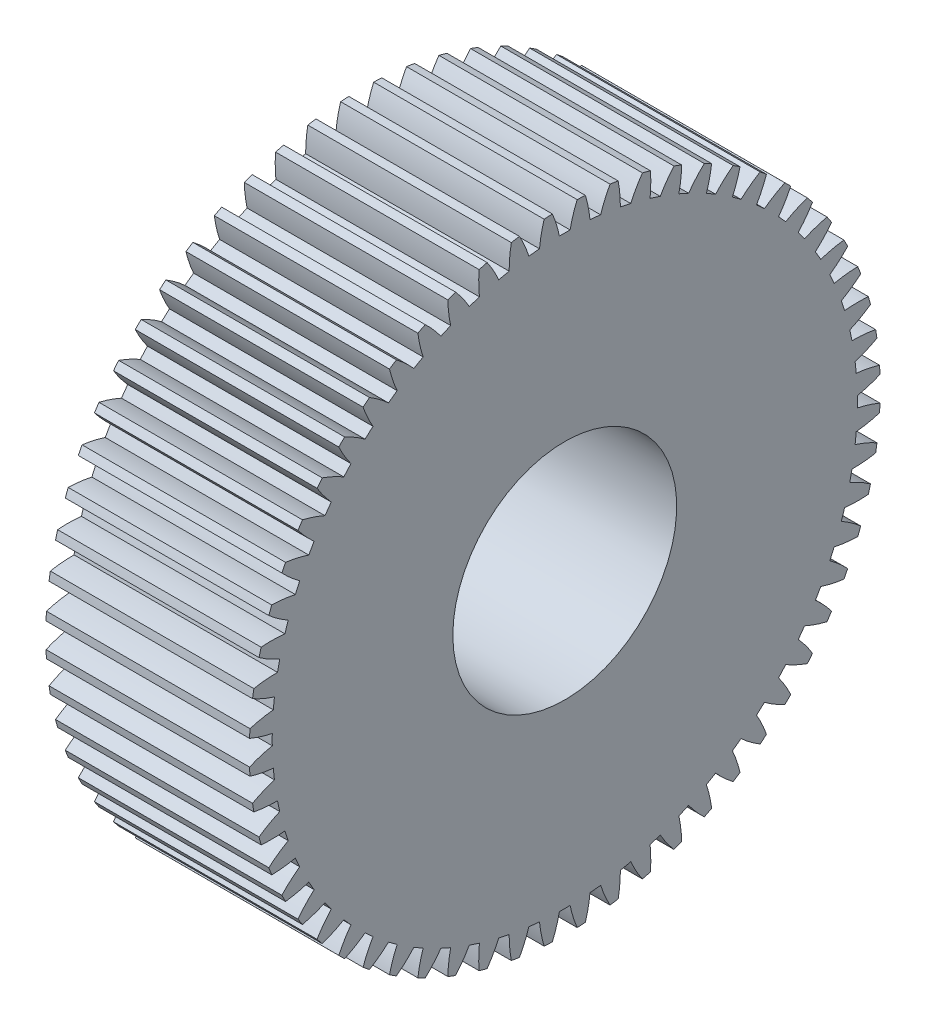
SolidWorks part; units mm, degrees
ref_plane "Plane1" through (0, 0, 0) normal (0, 0, 1) x (1, 0, 0)
ref_plane "Plane2" through (0, 0, 0) normal (0, 1, 0) x (1, 0, 0)
ref_plane "Plane3" through (0, 0, 0) normal (1, 0, 0) x (0, 0, -1)
other "Configuration Table"
sketch "HoldingSke" plane through (0, 0, 0) normal (0, 1, 0) x (1, 0, 0)
  line L0 (0, 0) -> (1, -1.7321)
  line L1 (-15, 0) -> (100, 0) construction
  line L2 (0, 0) -> (-2.1039, 2.3779)
  line L3 (0, 0) -> (-11.863, 4.5341)
  line L4 (0, 0) -> (4.318, 7.479)
  line L5 (0, 0) -> (-46.8476, -17.4728)
  line L6 (0, 0) -> (-8.2896, -5.593)
  line L7 (-2.1039, 2.3779) -> (8.6586, 51.2059)
  line L8 (-76.2, 54.61) -> (-74.4, 54.61)
  line L9 (-67.7845, 28.3722) -> (-49.3413, 33.142)
  line L10 (-76.2, 71.12) -> (104.1128, 71.12)
  line L11 (0, 0) -> (-10, 0)
  line L12 (-76.2, 101.6) -> (-76.181, 101.6)
  line L13 (24.9733, 27.94) -> (52.9518, 28.4284)
  line L14 (24.9733, 27.94) -> (24.9743, 27.94)
  line L15 (24.9733, 27.94) -> (100.4006, 29.5858)
  line L16 (-63.627, -0.5) -> (-12.827, -0.5)
  circle A0 centre (0, 0) radius 5.5
  circle A1 centre (0, 0) radius 14.374
  circle A2 centre (0, 0) radius 37.5
  circle A3 centre (0, 0) radius 5.5
  dimension "MHD" = 28.748
  dimension "Hub_dia" = 75
  dimension "Bore" = 11
  dimension "MBD" = 11
  dimension "Num_teeth" = 60
  dimension "Pitch" = 2
  dimension "Overall_len" = 50
  dimension "Show_teeth" = 60
  dimension "Thickness" = 10
  dimension "OAL" = 50.0001
  dimension "T_dim" = 1.8
  dimension "Ap" = 14.5
  dimension "H" = 19.05
  dimension "Pitch_radius" = 180.3128
  dimension "Width" = 10
  dimension "Backlash" = 0.019
  dimension "Addendum_fac" = 1
  dimension "Dedendum_fac" = 1.25
  dimension "Clearance_fac" = 0.25
  dimension "Dedendum_add" = 0.001
  dimension "Module" = 0.5
sketch "BasProSke" plane through (0, 0, 0) normal (0, 1, 0) x (1, 0, 0)
  line L0 (-10, 0) -> (60, 0) construction
  line L1 (0, 0) -> (0, 15.5)
  line L2 (0, 0) -> (10, 0)
  line L3 (10, 0) -> (10, 15.5)
  line L4 (10, 15.5) -> (0, 15.5)
  dimension "Thickness" = 10
  dimension "Diameter" = 31
revolve "Base-Revolve" add sketch "BasProSke" angle 360 about L0
sketch "TooCutSke" plane through (0, 0, 0) normal (1, 0, 0) x (0, 0, -1)
  line L1 (0, 0) -> (0, 107) construction
  line L2 (0, 0) -> (-0.4259, 14.994) construction
  line L3 (0, 0) -> (-1.5696, 29.9503) construction
  line L4 (-0.4259, 14.994) -> (-0.7848, 14.9751) construction
  arc A0 (0.2624, 14.3716) -> (-0.2624, 14.3716) centre (0, 0) ccw
  arc A1 (0.6193, 15.513) -> (-0.6193, 15.513) centre (0, 0) ccw
  circle A2 centre (0, 0) radius 15 construction
  circle A3 centre (0, 0) radius 14.5222 construction
  arc A4 (-0.2624, 14.3716) -> (-0.6193, 15.513) centre (-6.139, 13.1608) ccw
  arc A5 (0.6193, 15.513) -> (0.2624, 14.3716) centre (6.139, 13.1608) ccw
  dimension "Root_dia" = 28.748
  dimension "Overcut_dia" = 31.0508
  dimension "Pitch_dia" = 30
  dimension "Base_dia" = 29.0444
  dimension "Flank_rad" = 6
  dimension "Half_ang" = 3
  dimension "Half_CT" = 0.3594
extrude "ToothCut" cut sketch "TooCutSke" along normal through all
fillet "Breaks" [suppressed] radius 0.01
fillet "RootFillets" [suppressed] radius 0.126
pattern_circular "TeethCuts" count 60 every 6 about axis through (-10, 0, 0) along (1, 0, 0) of "ToothCut", "RootFillets", "Breaks"
sketch "HubNeaOneSke" plane through (0, 0, 0) normal (-1, 0, 0) x (0, 0, 1)
  circle A0 centre (0, 0) radius 14.374
  dimension "Diameter" = 28.748
extrude "HubNearOne" [suppressed] add sketch "HubNeaOneSke" along normal blind 40.0001
sketch "HubNeaBotSke" plane through (0, 0, 0) normal (-1, 0, 0) x (0, 0, 1)
  circle A0 centre (0, 0) radius 14.374
  dimension "Diameter" = 28.748
extrude "HubNearBoth" [suppressed] add sketch "HubNeaBotSke" along normal blind 20
ref_plane "FarPln" through (10, 0, 0) normal (1, 0, 0) x (0, 0, -1)
sketch "HubFarSke" plane through (10, 0, 0) normal (1, 0, 0) x (0, 0, -1)
  circle A0 centre (0, 0) radius 14.374
  dimension "Diameter" = 28.748
extrude "HubFar" [suppressed] add sketch "HubFarSke" along normal blind 20
sketch "BorSke" plane through (0, 0, 0) normal (1, 0, 0) x (0, 0, -1)
  circle A0 centre (0, 0) radius 5.5
  dimension "Diameter" = 11
extrude "Bore" cut sketch "BorSke" along normal mid plane 100.0001
sketch "KeySke" plane through (0, 0, 0) normal (1, 0, 0) x (0, 0, -1)
  line L0 (-2, 0) -> (-2, 7.3)
  line L1 (-2, 7.3) -> (2, 7.3)
  line L2 (2, 7.3) -> (2, 0)
  line L3 (0, 0) -> (0, 34) construction
  line L4 (-2, 0) -> (2, 0)
  dimension "Offset" = 7.3
  dimension "Width" = 4
extrude "Keyway" [suppressed] cut sketch "KeySke" along normal mid plane 100.0001
pattern_circular "Keyway2" [suppressed] count 2 every 90 about axis through (-10, 0, 0) along (1, 0, 0)
equation "' \"Module@HoldingSke\" = 6.35"
equation "' \"Num_teeth@HoldingSke\" = 12"
equation "' \"Ap@HoldingSke\" =  20"
equation "' \"Ap@HoldingSke\" = 20"
equation "' \"Width@HoldingSke\" = 0.5 * 25.4"
equation "' \"Hub_dia@HoldingSke\"= 1 * 25.4"
equation "' \"Hub_dia@HoldingSke\" = 1 * 25.4"
equation "' \"Overall_len@HoldingSke\" = 1.0 * 25.4"
equation "' \"Bore@HoldingSke\" = 0.75 * 25.4"
equation "' \"T_dim@HoldingSke\" = 0.1 * 25.4"
equation "' \"Width@KeySke\" = 0.25 * 25.4"
equation "' \"Show_teeth@HoldingSke\" = 13"
equation "' \"Backlash@HoldingSke\" = 0.009 * 25.4"
equation "' \"Addendum_fac@HoldingSke\" = 1.0"
equation "' \"Dedendum_fac@HoldingSke\" = 1.25"
equation "' \"Dedendum_add@HoldingSke\" = 0.00005 * 25.4"
equation "' \"Clearance_fac@HoldingSke\" = 0.25"
equation "\"Pitch@HoldingSke\" = 1 / \"Module@HoldingSke\""
equation "\"Overcut_dia@TooCutSke\" = (\"Num_teeth@HoldingSke\" + 2 * \"Addendum_fac@HoldingSke\") / \"Pitch@HoldingSke\" + 0.002 * 25.4"
equation "\"Pitch_dia@TooCutSke\" = \"Num_teeth@HoldingSke\" / \"Pitch@HoldingSke\""
equation "\"Base_dia@TooCutSke\" = \"Num_teeth@HoldingSke\" / \"Pitch@HoldingSke\" * cos((\"Ap@HoldingSke\"  * 3.14159265 / 180))"
equation "\"Root_dia@TooCutSke\" = (\"Num_teeth@HoldingSke\" + 2) / \"Pitch@HoldingSke\" - 2 * (\"Addendum_fac@HoldingSke\" + \"Dedendum_fac@HoldingSke\") / \"Pitch@HoldingSke\" - \"Dedendum_add@HoldingSke\" * 2"
equation "\"Half_ang@TooCutSke\" = 180 / \"Num_teeth@HoldingSke\""
equation "\"Half_CT@TooCutSke\" = \"Num_teeth@HoldingSke\" / \"Pitch@HoldingSke\" * sin((3.14159265 / 2 / \"Num_teeth@HoldingSke\")) / 2 - 7 * \"Backlash@HoldingSke\" / 4"
equation "\"Flank_rad@TooCutSke\" = \"Num_teeth@HoldingSke\" / \"Pitch@HoldingSke\" / 5"
equation "\"Radius@RootFillets\" = \"Clearance_fac@HoldingSke\" / \"Pitch@HoldingSke\" + \"Dedendum_add@HoldingSke\""
equation "\"Break_rad@Breaks\" = 0.02 / \"Pitch@HoldingSke\""
equation "\"Thickness@HoldingSke\" = \"Width@HoldingSke\""
equation "\"OAL@HoldingSke\" = \"Thickness@HoldingSke\""
equation "\"MHD@HoldingSke\" = (\"Num_teeth@HoldingSke\" + 2) / \"Pitch@HoldingSke\" - 2 * (\"Addendum_fac@HoldingSke\" + \"Dedendum_fac@HoldingSke\")  / \"Pitch@HoldingSke\" - \"Dedendum_add@HoldingSke\" * 2"
equation "\"MBD@HoldingSke\" = (\"Num_teeth@HoldingSke\" + 2) / \"Pitch@HoldingSke\" - 2 * (\"Addendum_fac@HoldingSke\" + \"Dedendum_fac@HoldingSke\")  / \"Pitch@HoldingSke\" - \"Dedendum_add@HoldingSke\" * 2 - 0.002 * 25.4"
equation "\"MHD@HoldingSke\" = ((sgn( \"MHD@HoldingSke\" - \"Hub_dia@HoldingSke\" )-1)*( \"MHD@HoldingSke\" - \"Hub_dia@HoldingSke\" ))/-2+ \"Hub_dia@HoldingSke\""
equation "\"MBD@HoldingSke\" = ((sgn( \"MBD@HoldingSke\" - \"Bore@HoldingSke\" )-1)*( \"MBD@HoldingSke\" - \"Bore@HoldingSke\" ))/-2+ \"Bore@HoldingSke\""
equation "\"OAL@HoldingSke\" = ((sgn( \"OAL@HoldingSke\" - \"Overall_len@HoldingSke\" )+1)*( \"OAL@HoldingSke\" - \"Overall_len@HoldingSke\" ))/2 + \"Overall_len@HoldingSke\" + 0.000002 * 25.4"
equation "\"Num_teeth@TeethCuts\" = int( \"Show_teeth@HoldingSke\" ) + 1"
equation "\"Num_teeth@TeethCuts\" = ((sgn( \"Num_teeth@TeethCuts\" - \"Num_teeth@HoldingSke\" )-1)*( \"Num_teeth@TeethCuts\" - \"Num_teeth@HoldingSke\" ))/-2+ \"Num_teeth@HoldingSke\""
equation "\"Num_teeth@TeethCuts\" = ((sgn( \"Num_teeth@TeethCuts\" - 2.0)+1)*( \"Num_teeth@TeethCuts\" - 2.0))/2 +2.0"
equation "\"Angle@TeethCuts\" = 360.0 / \"Num_teeth@HoldingSke\""
equation "\"Diameter@BasProSke\" = (\"Num_teeth@HoldingSke\" + 2 * \"Addendum_fac@HoldingSke\") / \"Pitch@HoldingSke\""
equation "\"Thickness@BasProSke\"  = \"Thickness@HoldingSke\""
equation "' \"Fillet_rad@BasProSke\" =  \"Thickness@HoldingSke\" * 0.05"
equation "' \"Fillet_rad@BasProSke\" = \"Thickness@HoldingSke\" * 0.05"
equation "\"MHD@HoldingSke\" = ((sgn( \"MHD@HoldingSke\" - \"Root_dia@TooCutSke\" )-1)*( \"MHD@HoldingSke\" - \"Root_dia@TooCutSke\" ))/-2+ \"Root_dia@TooCutSke\""
equation "\"Diameter@HubNeaOneSke\" = \"MHD@HoldingSke\""
equation "\"Length@HubNearOne\" = \"OAL@HoldingSke\" - \"Thickness@BasProSke\""
equation "\"Diameter@HubNeaBotSke\" = \"MHD@HoldingSke\""
equation "\"Length@HubNearBoth\" = ( \"OAL@HoldingSke\" - \"Thickness@BasProSke\" ) / 2.0"
equation "\"Thickness@FarPln\" = \"Thickness@BasProSke\""
equation "\"Diameter@HubFarSke\" = \"MHD@HoldingSke\""
equation "\"Length@HubFar\" = ( \"OAL@HoldingSke\" - \"Thickness@BasProSke\" ) / 2.0"
equation "\"Diameter@BorSke\" = \"MBD@HoldingSke\""
equation "\"D1@Bore\" = \"OAL@HoldingSke\" * 2.0"
equation "\"D1@Keyway\" = \"OAL@HoldingSke\" * 2.0"
equation "\"Offset@KeySke\" = \"T_dim@HoldingSke\" + \"MBD@HoldingSke\" / 2.0"
